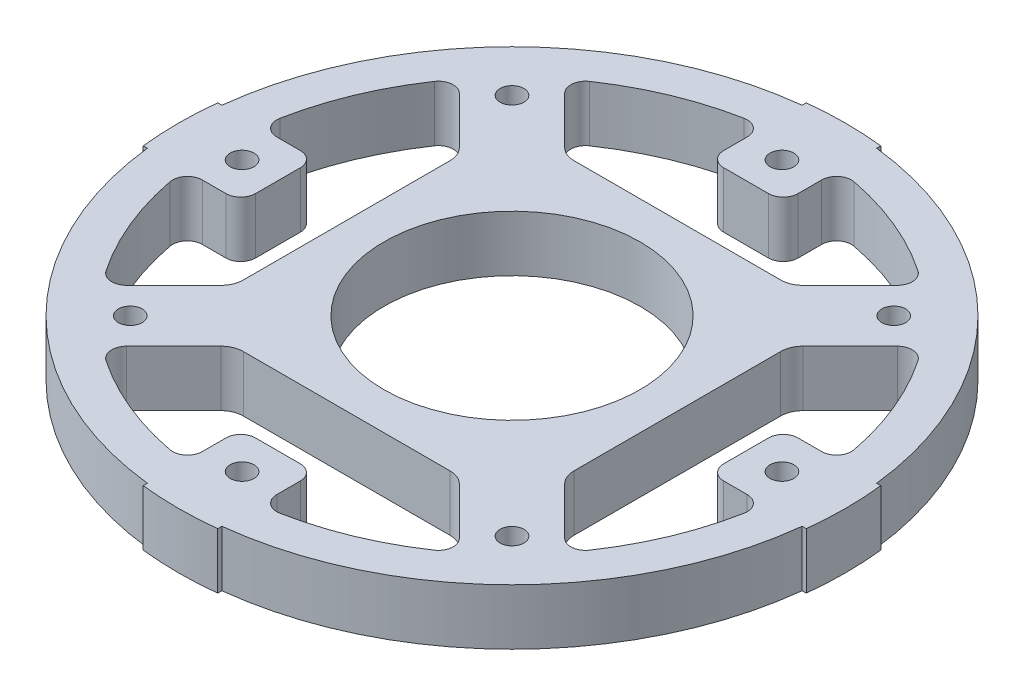
SolidWorks part; units mm, degrees
ref_plane "Front Plane" through (0, 0, 0) normal (0, 0, 1) x (1, 0, 0)
ref_plane "Top Plane" through (0, 0, 0) normal (0, 1, 0) x (1, 0, 0)
ref_plane "Right Plane" through (0, 0, 0) normal (1, 0, 0) x (0, 0, -1)
sketch "Sketch1" plane through (0, 0, 0) normal (0, 1, 0) x (1, 0, 0)
  line L0 (0, 0) -> (44.25, 0) construction
  line L1 (33.4302, 5) -> (36.5864, 5)
  line L2 (33.4302, -5) -> (36.5864, -5)
  line L3 (31.4302, 3) -> (31.4302, -3)
  line L4 (25.7601, -18.689) -> (29.406, -22.3349)
  line L5 (25.7601, -18.689) -> (18.689, -25.7601)
  line L6 (18.689, -25.7601) -> (22.3349, -29.406)
  line L7 (5, -33.4302) -> (5, -36.5864)
  line L8 (3, -31.4302) -> (-3, -31.4302)
  line L9 (-5, -33.4302) -> (-5, -36.5864)
  line L10 (-18.689, -25.7601) -> (-22.3349, -29.406)
  line L11 (-18.689, -25.7601) -> (-25.7601, -18.689)
  line L12 (-25.7601, -18.689) -> (-29.406, -22.3349)
  line L13 (-33.4302, -5) -> (-36.5864, -5)
  line L14 (-31.4302, -3) -> (-31.4302, 3)
  line L15 (-33.4302, 5) -> (-36.5864, 5)
  line L16 (-25.7601, 18.689) -> (-29.406, 22.3349)
  line L17 (-25.7601, 18.689) -> (-18.689, 25.7601)
  line L18 (-18.689, 25.7601) -> (-22.3349, 29.406)
  line L19 (-5, 33.4302) -> (-5, 36.5864)
  line L20 (-3, 31.4302) -> (3, 31.4302)
  line L21 (5, 33.4302) -> (5, 36.5864)
  line L22 (18.689, 25.7601) -> (22.3349, 29.406)
  line L23 (18.689, 25.7601) -> (25.7601, 18.689)
  line L24 (25.7601, 18.689) -> (29.406, 22.3349)
  line L25 (-5, 38.9302) -> (-5, 46.441) construction
  line L26 (5, 38.9302) -> (5, 47.4442) construction
  line L27 (-5, 43.9666) -> (-5, 44.5201)
  line L28 (5, 43.9666) -> (5, 44.5201)
  line L29 (43.9666, -5) -> (44.5201, -5)
  line L30 (43.9666, 5) -> (44.5201, 5)
  line L31 (-5, -43.9666) -> (-5, -44.5201)
  line L32 (5, -43.9666) -> (5, -44.5201)
  line L33 (-43.9666, 5) -> (-44.5201, 5)
  line L34 (-43.9666, -5) -> (-44.5201, -5)
  arc A0 (-43.9666, -5) -> (-5, -43.9666) centre (0, 0) ccw
  circle A1 centre (0, 0) radius 36.25 construction
  circle A2 centre (36.25, 0) radius 1.6
  arc A3 (38.5507, 7.3758) -> (32.475, 22.044) centre (0, 0) ccw
  circle A4 centre (25.6326, -25.6326) radius 1.6
  circle A5 centre (0, -36.25) radius 1.6
  circle A6 centre (-25.6326, -25.6326) radius 1.6
  circle A7 centre (-36.25, 0) radius 1.6
  circle A8 centre (-25.6326, 25.6326) radius 1.6
  circle A9 centre (0, 36.25) radius 1.6
  circle A10 centre (25.6326, 25.6326) radius 1.6
  arc A11 (-7.3758, 38.5507) -> (-22.044, 32.475) centre (0, 0) ccw
  arc A12 (22.044, 32.475) -> (7.3758, 38.5507) centre (0, 0) ccw
  arc A13 (-32.475, 22.044) -> (-38.5507, 7.3758) centre (0, 0) ccw
  arc A14 (-38.5507, -7.3758) -> (-32.475, -22.044) centre (0, 0) ccw
  arc A15 (-22.044, -32.475) -> (-7.3758, -38.5507) centre (0, 0) ccw
  arc A16 (7.3758, -38.5507) -> (22.044, -32.475) centre (0, 0) ccw
  arc A17 (32.475, -22.044) -> (38.5507, -7.3758) centre (0, 0) ccw
  arc A18 (-44.5201, 5) -> (-44.5201, -5) centre (0, 0) ccw
  arc A19 (-5, -44.5201) -> (5, -44.5201) centre (0, 0) ccw
  arc A20 (-5, 43.9666) -> (-43.9666, 5) centre (0, 0) ccw
  arc A21 (5, 44.5201) -> (-5, 44.5201) centre (0, 0) ccw
  arc A22 (43.9666, 5) -> (5, 43.9666) centre (0, 0) ccw
  arc A23 (44.5201, -5) -> (44.5201, 5) centre (0, 0) ccw
  arc A24 (5, -43.9666) -> (43.9666, -5) centre (0, 0) ccw
  arc A25 (-29.406, 22.3349) -> (-32.475, 22.044) centre (-30.8202, 20.9207) ccw
  arc A26 (-36.5864, 5) -> (-38.5507, 7.3758) centre (-36.5864, 7) cw
  arc A27 (-36.5864, -5) -> (-38.5507, -7.3758) centre (-36.5864, -7) ccw
  arc A28 (-29.406, -22.3349) -> (-32.475, -22.044) centre (-30.8202, -20.9207) cw
  arc A29 (-22.3349, -29.406) -> (-22.044, -32.475) centre (-20.9207, -30.8202) ccw
  arc A30 (-5, -36.5864) -> (-7.3758, -38.5507) centre (-7, -36.5864) cw
  arc A31 (5, -36.5864) -> (7.3758, -38.5507) centre (7, -36.5864) ccw
  arc A32 (22.3349, -29.406) -> (22.044, -32.475) centre (20.9207, -30.8202) cw
  arc A33 (29.406, -22.3349) -> (32.475, -22.044) centre (30.8202, -20.9207) ccw
  arc A34 (36.5864, -5) -> (38.5507, -7.3758) centre (36.5864, -7) cw
  arc A35 (36.5864, 5) -> (38.5507, 7.3758) centre (36.5864, 7) ccw
  arc A36 (29.406, 22.3349) -> (32.475, 22.044) centre (30.8202, 20.9207) cw
  arc A37 (22.3349, 29.406) -> (22.044, 32.475) centre (20.9207, 30.8202) ccw
  arc A38 (5, 36.5864) -> (7.3758, 38.5507) centre (7, 36.5864) cw
  arc A39 (-5, 36.5864) -> (-7.3758, 38.5507) centre (-7, 36.5864) ccw
  arc A40 (-22.3349, 29.406) -> (-22.044, 32.475) centre (-20.9207, 30.8202) cw
  arc A41 (-5, 33.4302) -> (-3, 31.4302) centre (-3, 33.4302) ccw
  arc A42 (3, 31.4302) -> (5, 33.4302) centre (3, 33.4302) ccw
  arc A43 (33.4302, 5) -> (31.4302, 3) centre (33.4302, 3) ccw
  arc A44 (33.4302, -5) -> (31.4302, -3) centre (33.4302, -3) cw
  arc A45 (5, -33.4302) -> (3, -31.4302) centre (3, -33.4302) ccw
  arc A46 (-3, -31.4302) -> (-5, -33.4302) centre (-3, -33.4302) ccw
  arc A47 (-33.4302, -5) -> (-31.4302, -3) centre (-33.4302, -3) ccw
  arc A48 (-31.4302, 3) -> (-33.4302, 5) centre (-33.4302, 3) ccw
  point P55 (0, 0)
  point P76 (0, 0)
  point P92 (38.9302, -5)
  point P95 (38.9302, 5)
  point P114 (31.4302, 5)
  point P117 (31.4302, -5)
  dimension "D1" = 88.5
  dimension "D2" = 72.5
  dimension "D3" = 3.2
  dimension "D4" = 5
  dimension "D8" = 89.6
  dimension "D10" = 2
  dimension "D11" = 2
  dimension "D5" = 7.5
  dimension "D6" = 10
  dimension "D7" = 8
  dimension "D9" = 4
extrude "Boss-Extrude1" add sketch "Sketch1" along normal blind 7.5
sketch "Sketch2" plane through (0, 7.5, 0) normal (0, 1, 0) x (1, 0, 0)
  line L0 (25.7601, 18.689) -> (18.689, 25.7601) construction
  line L1 (13.8863, 22.2) -> (-13.8863, 22.2)
  line L2 (-22.2, 13.8863) -> (-22.2, -13.8863)
  line L3 (-13.8863, -22.2) -> (13.8863, -22.2)
  line L4 (22.2, -13.8863) -> (22.2, 13.8863)
  line L5 (18.689, -25.7601) -> (25.7601, -18.689) construction
  line L6 (-25.7601, -18.689) -> (-18.689, -25.7601) construction
  line L7 (-18.689, 25.7601) -> (-25.7601, 18.689) construction
  line L8 (25.7601, 18.689) -> (18.689, 25.7601)
  line L9 (18.689, -25.7601) -> (25.7601, -18.689)
  line L10 (-25.7601, -18.689) -> (-18.689, -25.7601)
  line L11 (-18.689, 25.7601) -> (-25.7601, 18.689)
  line L12 (-25.7601, 18.689) -> (-23.0787, 16.0076)
  line L13 (-18.689, 25.7601) -> (-16.0076, 23.0787)
  line L14 (18.689, 25.7601) -> (16.0076, 23.0787)
  line L15 (25.7601, 18.689) -> (23.0787, 16.0076)
  line L16 (25.7601, -18.689) -> (23.0787, -16.0076)
  line L17 (18.689, -25.7601) -> (16.0076, -23.0787)
  line L18 (-25.7601, -18.689) -> (-23.0787, -16.0076)
  line L19 (-18.689, -25.7601) -> (-16.0076, -23.0787)
  circle A0 centre (0, 0) radius 17.2
  circle A1 centre (0, 0) radius 22.2 construction
  arc A2 (-23.0787, -16.0076) -> (-22.2, -13.8863) centre (-25.2, -13.8863) ccw
  arc A3 (-16.0076, -23.0787) -> (-13.8863, -22.2) centre (-13.8863, -25.2) cw
  arc A4 (16.0076, -23.0787) -> (13.8863, -22.2) centre (13.8863, -25.2) ccw
  arc A5 (23.0787, -16.0076) -> (22.2, -13.8863) centre (25.2, -13.8863) cw
  arc A6 (23.0787, 16.0076) -> (22.2, 13.8863) centre (25.2, 13.8863) ccw
  arc A7 (16.0076, 23.0787) -> (13.8863, 22.2) centre (13.8863, 25.2) cw
  arc A8 (-16.0076, 23.0787) -> (-13.8863, 22.2) centre (-13.8863, 25.2) ccw
  arc A9 (-23.0787, 16.0076) -> (-22.2, 13.8863) centre (-25.2, 13.8863) cw
  dimension "D1" = 34.4
  dimension "D2" = 5
  dimension "D3" = 3
extrude "Boss-Extrude2" add sketch "Sketch2" against normal blind 7.5
